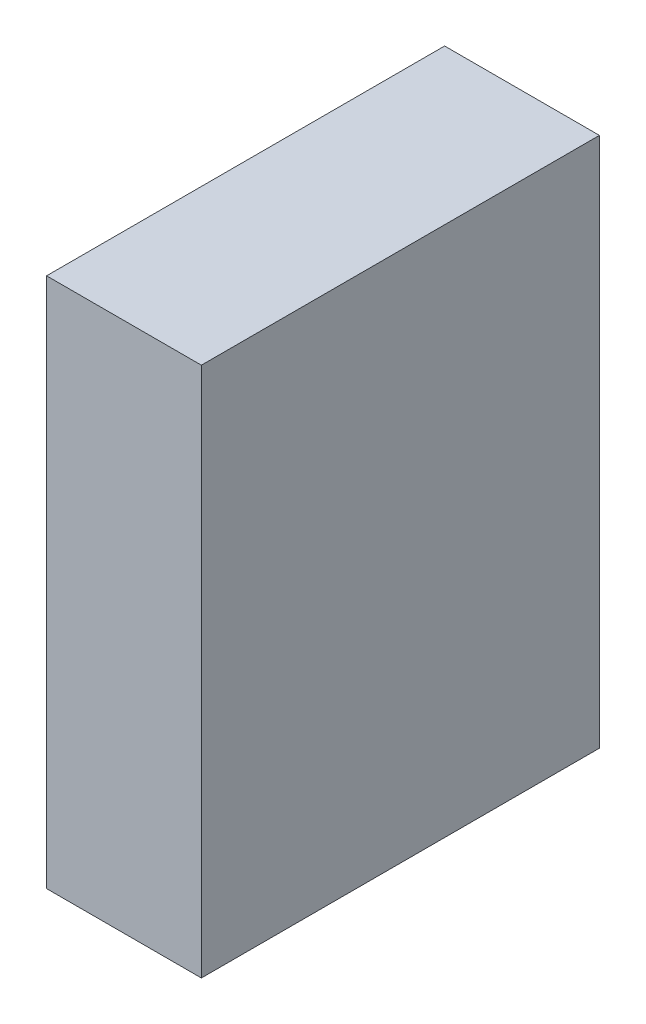
SolidWorks part; units mm, degrees
ref_plane "前视基准面" through (0, 0, 0) normal (0, 0, 1) x (1, 0, 0)
ref_plane "上视基准面" through (0, 0, 0) normal (0, 1, 0) x (1, 0, 0)
ref_plane "右视基准面" through (0, 0, 0) normal (1, 0, 0) x (0, 0, -1)
sketch "草图1" plane through (0, 0, 0) normal (0, 0, 1) x (1, 0, 0)
  line L1 (-26.3529, 57.8529) -> (8.6471, 57.8529)
  line L2 (-26.3529, 57.8529) -> (-26.3529, -62.1471)
  line L3 (-26.3529, -62.1471) -> (8.6471, -62.1471)
  line L4 (8.6471, 57.8529) -> (8.6471, -62.1471)
  dimension "D1" = 35
  dimension "D2" = 120
extrude "凸台-拉伸1" add sketch "草图1" along normal blind 90
sketch "草图2" plane through (0, 0, 0) normal (0, 0, -1) x (-1, 0, 0)
  line L0 (8.8529, 57.8529) -> (8.8529, -62.1471) construction
  line L1 (-8.6471, 57.8529) -> (26.3529, 57.8529) construction
  line L2 (26.3529, -62.1471) -> (-8.6471, -62.1471) construction
  circle A0 centre (8.8529, 52.8529) radius 2.1
  circle A1 centre (8.8529, -55.1471) radius 2.1
  dimension "D1" = 108
  dimension "D2" = 5
extrude "切除-拉伸1" cut sketch "草图2" against normal blind 5
